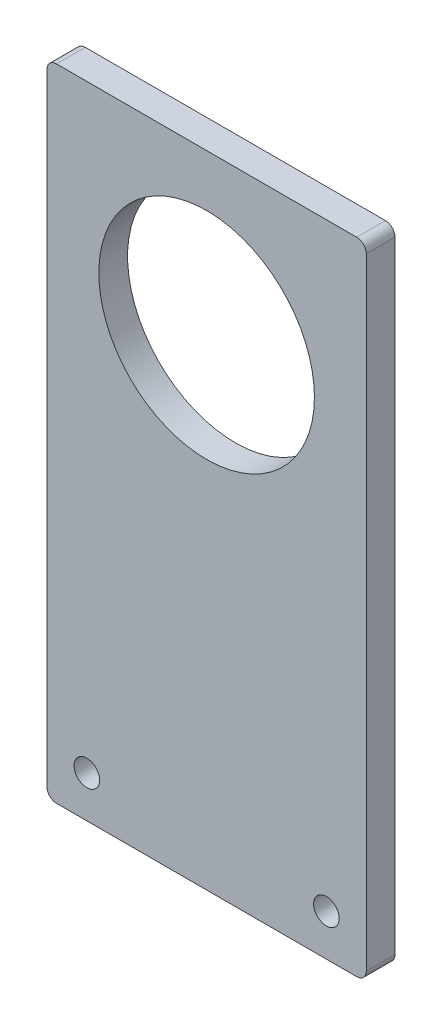
SolidWorks part; units mm, degrees
ref_plane "前视基准面" through (0, 0, 0) normal (0, 0, 1) x (1, 0, 0)
ref_plane "上视基准面" through (0, 0, 0) normal (0, 1, 0) x (1, 0, 0)
ref_plane "右视基准面" through (0, 0, 0) normal (1, 0, 0) x (0, 0, -1)
sketch "草图1" plane through (0, 0, 0) normal (0, 0, 1) x (1, 0, 0)
  line L0 (10.1, 0) -> (10.1, -21.913) construction
  line L1 (0.7, 0) -> (19.5, 0)
  line L2 (0, -0.7) -> (0, -39.6)
  line L3 (0.7, -40.3) -> (19.5, -40.3)
  line L4 (20.2, -0.7) -> (20.2, -39.6)
  arc A0 (19.5, -40.3) -> (20.2, -39.6) centre (19.5, -39.6) ccw
  arc A1 (0.7, -40.3) -> (0, -39.6) centre (0.7, -39.6) cw
  arc A2 (0.7, 0) -> (0, -0.7) centre (0.7, -0.7) ccw
  arc A3 (19.5, 0) -> (20.2, -0.7) centre (19.5, -0.7) cw
  circle A4 centre (10.1, -10.1) radius 6.75
  point P7 (20.2, -40.3)
  point P12 (0, 0)
  point P15 (20.2, 0)
  dimension "D3" = 0.7
  dimension "D4" = 13.5
  dimension "D1" = 40.3
  dimension "D2" = 20.2
  dimension "D5" = 10.1
extrude "凸台-拉伸1" add sketch "草图1" along normal blind 1.8
sketch "草图2" plane through (0, 0, 1.8) normal (0, 0, 1) x (1, 0, 0)
  line L0 (10.1, 0) -> (10.1, -23.9064) construction
  line L1 (19.5, 0) -> (0.7, 0) construction
  line L2 (20.2, -39.6) -> (20.2, -0.7) construction
  line L3 (0.7, -40.3) -> (19.5, -40.3) construction
  circle A0 centre (17.6, -2.6) radius 0.8
  circle A1 centre (17.6, -37.6) radius 0.8
  circle A2 centre (2.6, -37.6) radius 0.8
  circle A3 centre (2.6, -2.6) radius 0.8
  dimension "D1" = 2.6
  dimension "D3" = 1.6
  dimension "D4" = 2.7
  dimension "D5" = 1.6
  dimension "D2" = 2.6
extrude "切除-拉伸1" cut sketch "草图2" against normal blind 2
sketch "草图3" plane through (0, 0, 0) normal (0, 0, -1) x (-1, 0, 0)
  circle A0 centre (-17.6, -2.6) radius 1.75
  circle A1 centre (-2.6, -2.6) radius 1.75
  circle A2 centre (-17.6, -37.6) radius 1.75
  circle A3 centre (-2.6, -37.6) radius 1.75
  dimension "D1" = 3.5
  dimension "D2" = 3.5
  dimension "D3" = 3.5
  dimension "D4" = 3.5
extrude "切除-拉伸2" cut sketch "草图3" against normal blind 0.5
sketch "草图4" plane through (0, 0, 0) normal (0, 0, -1) x (-1, 0, 0)
  line L0 (-0.7, -0.1) -> (-19.5, -0.1)
  line L1 (-20.1, -0.7) -> (-20.1, -39.6)
  line L2 (-19.5, -40.2) -> (-0.7, -40.2)
  line L3 (-0.1, -39.6) -> (-0.1, -0.7)
  line L4 (-19.5, -40.3) -> (-0.7, -40.3)
  line L5 (0, -39.6) -> (0, -0.7)
  line L6 (-0.7, 0) -> (-19.5, 0)
  line L7 (-20.2, -0.7) -> (-20.2, -39.6)
  line L8 (-19.5, -40.3) -> (-0.7, -40.3)
  line L9 (0, -39.6) -> (0, -0.7)
  line L10 (-0.7, 0) -> (-19.5, 0)
  line L11 (-20.2, -0.7) -> (-20.2, -39.6)
  arc A0 (-19.5, -0.1) -> (-20.1, -0.7) centre (-19.5, -0.7) ccw
  arc A1 (-20.1, -39.6) -> (-19.5, -40.2) centre (-19.5, -39.6) ccw
  arc A2 (-0.7, -40.2) -> (-0.1, -39.6) centre (-0.7, -39.6) ccw
  arc A3 (-0.1, -0.7) -> (-0.7, -0.1) centre (-0.7, -0.7) ccw
  arc A4 (-20.2, -39.6) -> (-19.5, -40.3) centre (-19.5, -39.6) ccw
  arc A5 (-0.7, -40.3) -> (0, -39.6) centre (-0.7, -39.6) ccw
  arc A6 (0, -0.7) -> (-0.7, 0) centre (-0.7, -0.7) ccw
  arc A7 (-19.5, 0) -> (-20.2, -0.7) centre (-19.5, -0.7) ccw
  arc A8 (-20.2, -39.6) -> (-19.5, -40.3) centre (-19.5, -39.6) ccw
  arc A9 (-0.7, -40.3) -> (0, -39.6) centre (-0.7, -39.6) ccw
  arc A10 (0, -0.7) -> (-0.7, 0) centre (-0.7, -0.7) ccw
  arc A11 (-19.5, 0) -> (-20.2, -0.7) centre (-19.5, -0.7) ccw
  dimension "D1" = 0
  dimension "D2" = 0.1
extrude "切除-拉伸4" cut sketch "草图4" against normal blind 10
sketch "草图6" plane through (0, 0, 0) normal (0, 0, -1) x (-1, 0, 0)
  circle A0 centre (-17.6, -2.6) radius 1.75
  circle A1 centre (-2.6, -2.6) radius 1.75
extrude "凸台-拉伸2" add sketch "草图6" against normal up to vertex (1.8 mm away) up to point (20.1, -0.7, 1.8)
